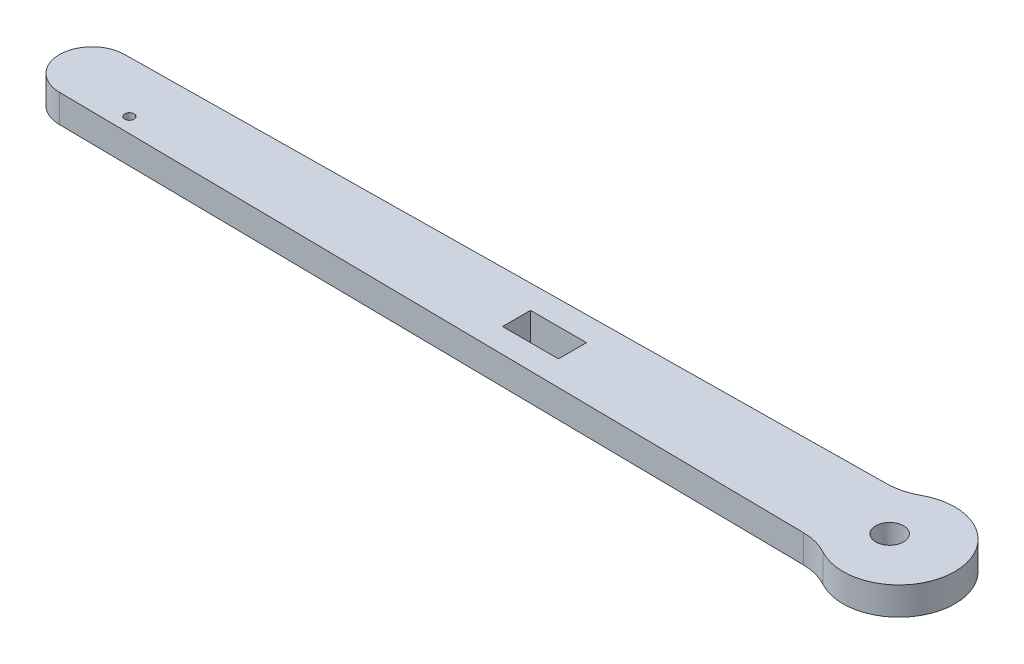
SolidWorks part; units mm, degrees
ref_plane "Alzado" through (0, 0, 0) normal (0, 0, 1) x (1, 0, 0)
ref_plane "Planta" through (0, 0, 0) normal (0, 1, 0) x (1, 0, 0)
ref_plane "Vista lateral" through (0, 0, 0) normal (1, 0, 0) x (0, 0, -1)
sketch "Croquis1" plane through (0, 0, 0) normal (0, 0, 1) x (1, 0, 0)
  line L0 (41811.2646, -420.5449) -> (41892.0315, -419.5418)
  line L1 (41811.2646, -427.5449) -> (41892.0315, -428.5481)
  line L7 (41856.7646, -422.5449) -> (41862.7646, -422.5449)
  line L8 (41856.7646, -422.5449) -> (41856.7646, -425.5449)
  line L9 (41856.7646, -425.5449) -> (41862.7646, -425.5449)
  line L10 (41862.7646, -422.5449) -> (41862.7646, -425.5449)
  arc A0 (41811.2646, -420.5449) -> (41811.2646, -427.5449) centre (41811.2646, -424.0449) ccw
  circle A1 centre (41817.2646, -426.0449) radius 0.5
  arc A3 (41894.8624, -429.2963) -> (41894.8624, -418.7936) centre (41897.7646, -424.0449) ccw
  arc A4 (41892.0315, -419.5418) -> (41894.8624, -418.7936) centre (41891.9601, -413.5422) ccw
  arc A5 (41894.8624, -429.2963) -> (41892.0315, -428.5481) centre (41891.9601, -434.5477) ccw
  circle A6 centre (41896.7646, -424.0449) radius 1.5
extrude "Saliente-Extruir1" add sketch "Croquis1" along normal blind 3
move or copy body "Sólido-Mover/Copiar1" bodies to move or copy 101 copy no rotation origin (0, -424.0449, 1.5) rotation axis (-1, 0, 0) rotation angle 90
